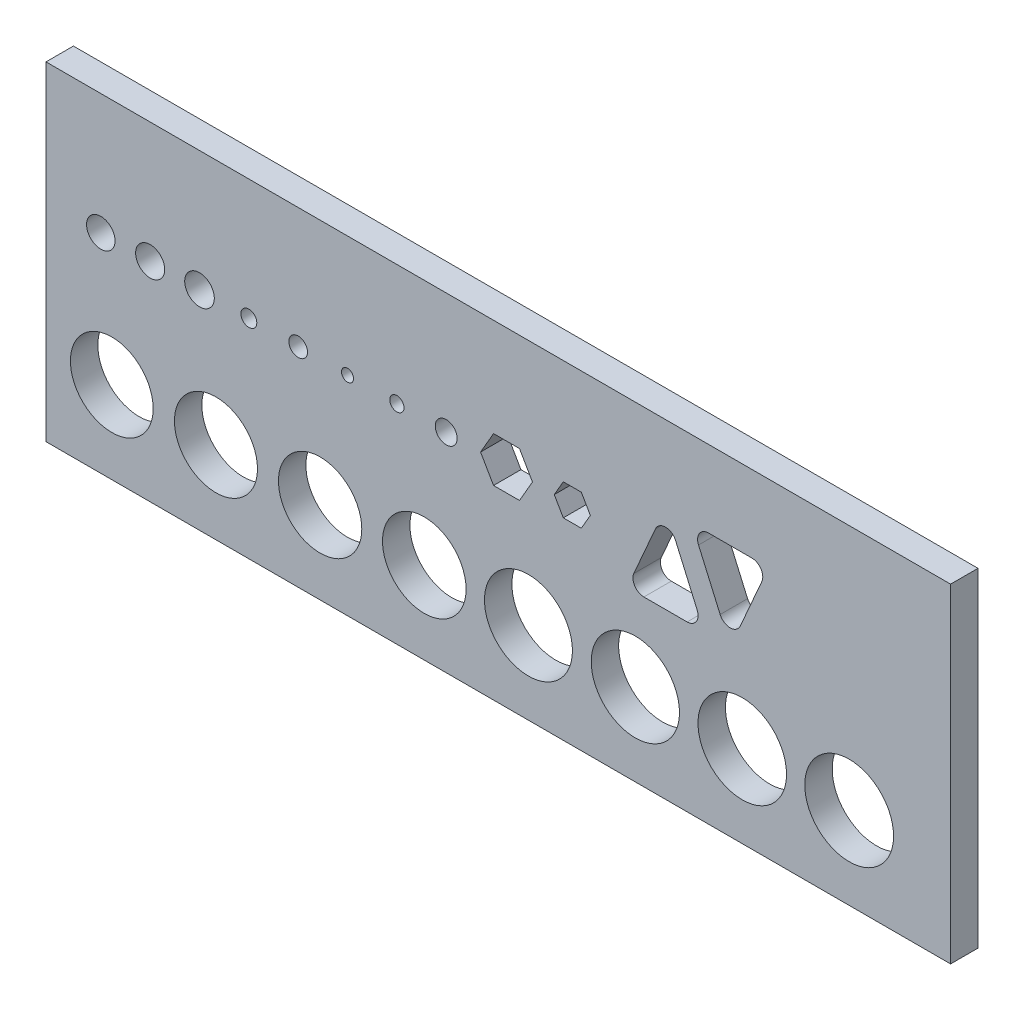
SolidWorks part; units mm, degrees
ref_plane "Front Plane" through (0, 0, 0) normal (0, 0, 1) x (1, 0, 0)
ref_plane "Top Plane" through (0, 0, 0) normal (0, 1, 0) x (1, 0, 0)
ref_plane "Right Plane" through (0, 0, 0) normal (1, 0, 0) x (0, 0, -1)
ref_plane "Plane1" through (0, 0, 300) normal (0, 0, 1) x (1, 0, 0)
sketch "Sketch1" plane through (0, 0, 300) normal (0, 0, 1) x (1, 0, 0)
  line L0 (300, 300) -> (465, 300)
  line L1 (465, 300) -> (465, 360)
  line L2 (465, 360) -> (300, 360)
  line L3 (300, 360) -> (300, 300)
  line L4 (388.7343, 338) -> (386.3671, 342.1)
  line L5 (386.3671, 342.1) -> (381.6329, 342.1)
  line L6 (381.6329, 342.1) -> (379.2657, 338)
  line L7 (379.2657, 338) -> (381.6329, 333.9)
  line L8 (381.6329, 333.9) -> (386.3671, 333.9)
  line L9 (386.3671, 333.9) -> (388.7343, 338)
  line L10 (399.2909, 338) -> (397.6454, 340.85)
  line L11 (397.6454, 340.85) -> (394.3546, 340.85)
  line L12 (394.3546, 340.85) -> (392.7091, 338)
  line L13 (392.7091, 338) -> (394.3546, 335.15)
  line L14 (394.3546, 335.15) -> (397.6454, 335.15)
  line L15 (397.6454, 335.15) -> (399.2909, 338)
  line L16 (409.058, 330) -> (416.942, 330)
  line L17 (418.7743, 332.8016) -> (414.8323, 341.8119)
  line L18 (411.1677, 341.8119) -> (407.2257, 332.8016)
  line L19 (426.6323, 334.1881) -> (430.5743, 343.1984)
  line L20 (428.742, 346) -> (420.858, 346)
  line L21 (419.0257, 343.1984) -> (422.9677, 334.1881)
  circle A0 centre (312, 315) radius 7.55
  circle A1 centre (331, 315) radius 7.575
  circle A2 centre (350, 315) radius 7.6
  circle A3 centre (369, 315) radius 7.625
  circle A4 centre (388, 315) radius 8.025
  circle A5 centre (407.5, 315) radius 8.05
  circle A6 centre (427, 315) radius 8.075
  circle A7 centre (446.5, 315) radius 8.1
  circle A8 centre (310, 338) radius 2.6
  circle A9 centre (319, 338) radius 2.65
  circle A10 centre (328, 338) radius 2.7
  circle A11 centre (337, 338) radius 1.45
  circle A12 centre (346, 338) radius 1.7
  circle A13 centre (355, 338) radius 1.1
  circle A14 centre (364, 338) radius 1.3
  circle A15 centre (373, 338) radius 2
  arc A16 (407.2257, 332.8016) -> (409.058, 330) centre (409.058, 332) ccw
  arc A17 (416.942, 330) -> (418.7743, 332.8016) centre (416.942, 332) ccw
  arc A18 (414.8323, 341.8119) -> (411.1677, 341.8119) centre (413, 341.0102) ccw
  arc A19 (422.9677, 334.1881) -> (426.6323, 334.1881) centre (424.8, 334.9898) ccw
  arc A20 (430.5743, 343.1984) -> (428.742, 346) centre (428.742, 344) ccw
  arc A21 (420.858, 346) -> (419.0257, 343.1984) centre (420.858, 344) ccw
extrude "Boss-Extrude1" add sketch "Sketch1" along normal blind 5
